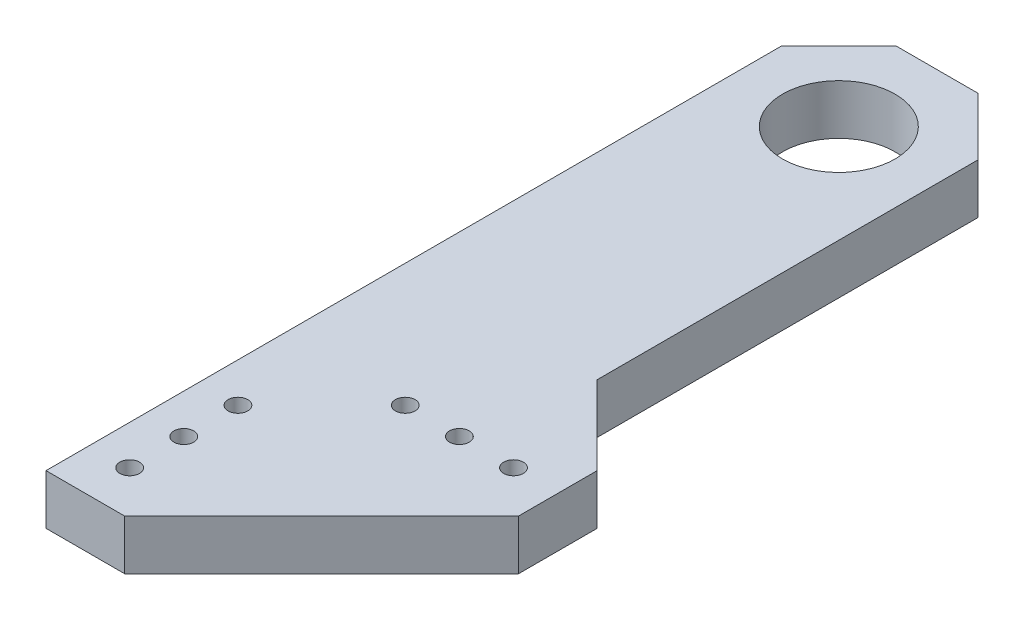
SolidWorks part; units mm, degrees
ref_plane "Front Plane" through (0, 0, 0) normal (0, 0, 1) x (1, 0, 0)
ref_plane "Top Plane" through (0, 0, 0) normal (0, 1, 0) x (1, 0, 0)
ref_plane "Right Plane" through (0, 0, 0) normal (1, 0, 0) x (0, 0, -1)
sketch "Sketch1" plane through (0, 0, 0) normal (0, 1, 0) x (1, 0, 0)
  line L0 (-10, -60) -> (10, -60)
  line L1 (10, -60) -> (60, -10)
  line L2 (60, -10) -> (60, 10)
  line L4 (25.3553, 141.37) -> (4.6447, 141.37)
  line L5 (4.6447, 141.37) -> (-10, 126.7253)
  line L6 (-10, 126.7253) -> (-10, -60)
  line L7 (15, 116.37) -> (15, 141.37) construction
  line L8 (15, 141.37) -> (15, 116.37) construction
  line L9 (15, 116.37) -> (-2.6777, 134.0477) construction
  line L10 (15, 116.37) -> (32.6777, 134.0477) construction
  line L11 (15, 116.37) -> (-10, 116.37) construction
  line L12 (60, 10) -> (-10, 10) construction
  line L13 (25.3553, 141.37) -> (40, 126.7253)
  line L14 (0, -60) -> (0, -51.25) construction
  line L15 (10, -10) -> (-10, -10) construction
  line L16 (10, -10) -> (10, 10) construction
  line L17 (10, 10) -> (-10, 10) construction
  line L18 (-10, -10) -> (-10, 10) construction
  line L19 (10, -10) -> (-10, 10) construction
  line L20 (10, 10) -> (-10, -10) construction
  line L21 (0, -46.25) -> (0, -37.5) construction
  line L22 (0, -32.5) -> (0, -23.75) construction
  line L23 (0, -18.75) -> (0, -10) construction
  line L24 (18.75, 0) -> (10, 0) construction
  line L25 (23.75, 0) -> (32.5, 0) construction
  line L26 (37.5, 0) -> (46.25, 0) construction
  line L27 (51.25, 0) -> (60, 0) construction
  line L28 (40, 126.7253) -> (40, 30)
  line L29 (40, 30) -> (60, 10)
  line L30 (15, 116.37) -> (40, 116.37) construction
  circle A0 centre (15, 116.37) radius 14.2875
  circle A1 centre (48.75, 0) radius 2.5
  circle A2 centre (35, 0) radius 2.5
  circle A3 centre (21.25, 0) radius 2.5
  circle A4 centre (0, -48.75) radius 2.5
  circle A5 centre (0, -35) radius 2.5
  circle A6 centre (0, -21.25) radius 2.5
  point P2 (60, 0)
  point P8 (0, -60)
  point P33 (0, 0)
  point P50 (35, -35)
  point P51 (32.6777, 134.0477)
  dimension "D4" = 28.575
  dimension "D5" = 5
  dimension "D7" = 25
  dimension "D1" = 45
  dimension "D2" = 20
  dimension "D3" = 50
  dimension "D6" = 106.37
extrude "Boss-Extrude1" add sketch "Sketch1" along normal mid plane 12.7
